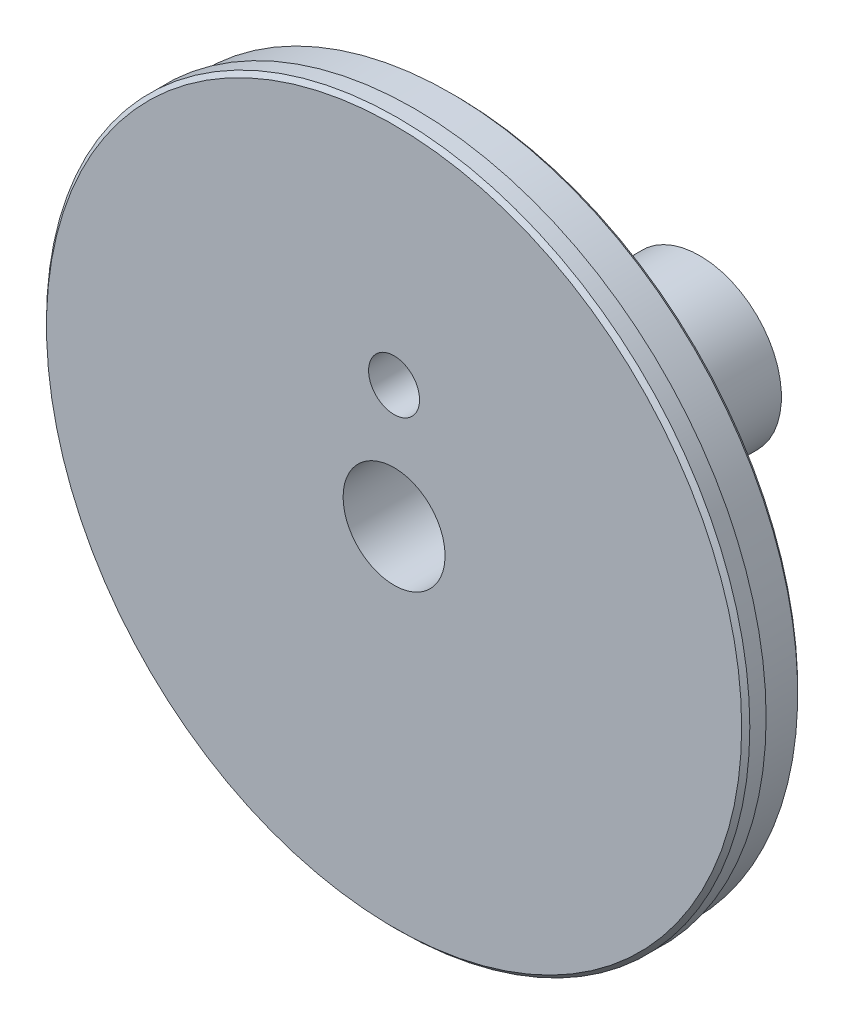
SolidWorks part; units mm, degrees
ref_plane "Front Plane" through (0, 0, 0) normal (0, 0, 1) x (1, 0, 0)
ref_plane "Top Plane" through (0, 0, 0) normal (0, 1, 0) x (1, 0, 0)
ref_plane "Right Plane" through (0, 0, 0) normal (1, 0, 0) x (0, 0, -1)
sketch "Sketch1" plane through (0, 0, 0) normal (0, 0, 1) x (1, 0, 0)
  circle A0 centre (0, 0) radius 17.25
  dimension "D1" = 34.5
extrude "Boss-Extrude1" add sketch "Sketch1" along normal blind 1
sketch "Sketch2" plane through (0, 0, 0) normal (0, 0, -1) x (-1, 0, 0)
  circle A0 centre (0, 0) radius 17
  dimension "D1" = 34
extrude "Boss-Extrude2" add sketch "Sketch2" along normal blind 2
sketch "Sketch3" plane through (0, 0, -2) normal (0, 0, -1) x (-1, 0, 0)
  circle A0 centre (0, 0) radius 9
  dimension "D1" = 18
extrude "Boss-Extrude3" add sketch "Sketch3" along normal blind 3
sketch "Sketch4" plane through (0, 0, -5) normal (0, 0, -1) x (-1, 0, 0)
  circle A0 centre (0, 0) radius 4
  dimension "D1" = 8
extrude "Boss-Extrude4" add sketch "Sketch4" along normal blind 9
sketch "Sketch5" plane through (0, 0, -14) normal (0, 0, -1) x (-1, 0, 0)
  circle A0 centre (0, 0) radius 2.5
  dimension "D1" = 5
extrude "Cut-Extrude1" cut sketch "Sketch5" against normal through all
sketch "Sketch6" plane through (0, 0, -5) normal (0, 0, -1) x (-1, 0, 0)
  circle A0 centre (0, 6) radius 1.25
  dimension "D1" = 2.5
  dimension "D2" = 6
extrude "Cut-Extrude2" cut sketch "Sketch6" against normal through all
chamfer "Chamfer1" distance 0.2 angle 45 4 edges at (-2.5, 0, -14) (-9, 0, -5) (-17, 0, -2) (17.25, 0, 1)
